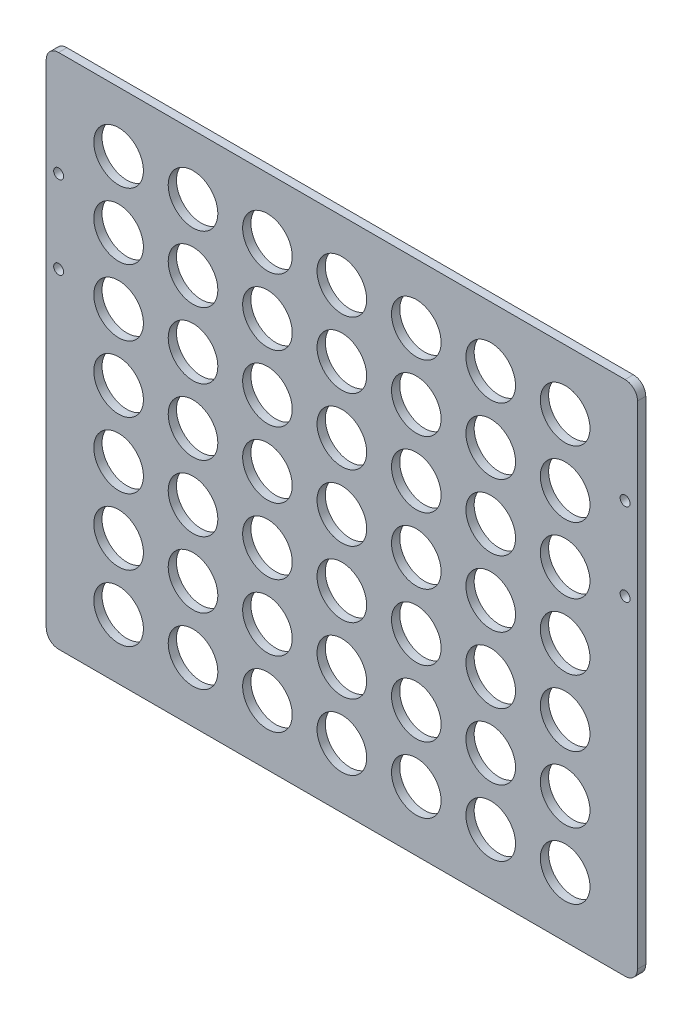
SolidWorks part; units mm, degrees
material "Thornel Mat VMA"
ref_plane "前视基准面" through (0, 0, 0) normal (0, 0, 1) x (1, 0, 0)
ref_plane "上视基准面" through (0, 0, 0) normal (0, 1, 0) x (1, 0, 0)
ref_plane "右视基准面" through (0, 0, 0) normal (1, 0, 0) x (0, 0, -1)
sketch "草图1" plane through (0, 0, 0) normal (0, 0, 1) x (1, 0, 0)
  line L1 (71.5, -62.5) -> (-71.5, -62.5)
  line L2 (71.5, -62.5) -> (71.5, 62.5)
  line L3 (71.5, 62.5) -> (-71.5, 62.5)
  line L4 (-71.5, -62.5) -> (-71.5, 62.5)
  line L5 (71.5, -62.5) -> (-71.5, 62.5) construction
  line L6 (71.5, 62.5) -> (-71.5, -62.5) construction
  point P0 (0, 0)
  dimension "D1" = 143
  dimension "D2" = 125
extrude "凸台-拉伸1" add sketch "草图1" along normal blind 2
fillet "圆角1" radius 3 4 edges at (71.5, 62.5, 1) (71.5, -62.5, 1) (-71.5, -62.5, 1) (-71.5, 62.5, 1)
sketch "草图2" plane through (0, 0, 0) normal (0, 0, -1) x (-1, 0, 0)
  line L0 (-71.5, 0) -> (71.5, 0) construction
  line L1 (-71.5, -59.5) -> (-71.5, 59.5) construction
  line L2 (71.5, 59.5) -> (71.5, -59.5) construction
  line L3 (0, 62.5) -> (0, -62.5) construction
  line L4 (-68.5, 62.5) -> (68.5, 62.5) construction
  line L5 (68.5, -62.5) -> (-68.5, -62.5) construction
  circle A0 centre (0, 0) radius 6
  circle A1 centre (18, 0) radius 6
  circle A2 centre (36, 0) radius 6
  circle A3 centre (54, 0) radius 6
  circle A4 centre (-54, 0) radius 6
  circle A5 centre (-36, 0) radius 6
  circle A6 centre (-18, 0) radius 6
  circle A7 centre (0, 16) radius 6
  circle A8 centre (18, 16) radius 6
  circle A9 centre (36, 16) radius 6
  circle A10 centre (54, 16) radius 6
  circle A11 centre (-54, 16) radius 6
  circle A12 centre (-36, 16) radius 6
  circle A13 centre (-18, 16) radius 6
  circle A14 centre (0, 32) radius 6
  circle A15 centre (18, 32) radius 6
  circle A16 centre (36, 32) radius 6
  circle A17 centre (54, 32) radius 6
  circle A18 centre (-54, 32) radius 6
  circle A19 centre (-36, 32) radius 6
  circle A20 centre (-18, 32) radius 6
  circle A21 centre (0, 48) radius 6
  circle A22 centre (18, 48) radius 6
  circle A23 centre (36, 48) radius 6
  circle A24 centre (54, 48) radius 6
  circle A25 centre (-54, 48) radius 6
  circle A26 centre (-36, 48) radius 6
  circle A27 centre (-18, 48) radius 6
  circle A28 centre (0, -16) radius 6
  circle A29 centre (18, -16) radius 6
  circle A30 centre (36, -16) radius 6
  circle A31 centre (54, -16) radius 6
  circle A32 centre (-54, -16) radius 6
  circle A33 centre (-36, -16) radius 6
  circle A34 centre (-18, -16) radius 6
  circle A35 centre (0, -32) radius 6
  circle A36 centre (18, -32) radius 6
  circle A37 centre (36, -32) radius 6
  circle A38 centre (54, -32) radius 6
  circle A39 centre (-54, -32) radius 6
  circle A40 centre (-36, -32) radius 6
  circle A41 centre (-18, -32) radius 6
  circle A42 centre (0, -48) radius 6
  circle A43 centre (18, -48) radius 6
  circle A44 centre (36, -48) radius 6
  circle A45 centre (54, -48) radius 6
  circle A46 centre (-54, -48) radius 6
  circle A47 centre (-36, -48) radius 6
  circle A48 centre (-18, -48) radius 6
  dimension "D1" = 12
  dimension "D2" = 4
extrude "切除-拉伸1" cut sketch "草图2" against normal blind 10
sketch "草图3" plane through (0, 0, 2) normal (0, 0, 1) x (1, 0, 0)
  line L1 (0, 62.5) -> (0, -62.5) construction
  line L2 (68.5, 62.5) -> (-68.5, 62.5) construction
  line L3 (-68.5, -62.5) -> (68.5, -62.5) construction
  line L4 (-71.5, 0) -> (71.5, 0) construction
  line L5 (-71.5, 59.5) -> (-71.5, -59.5) construction
  line L6 (71.5, -59.5) -> (71.5, 59.5) construction
  circle A0 centre (-68.5, 37.1255) radius 1.2 construction
  circle A1 centre (-68.5, 17.1255) radius 1.2 construction
  circle A2 centre (-68.5, 37.1255) radius 1.2
  circle A3 centre (-68.5, 17.1255) radius 1.2
  circle A4 centre (68.5, 17.1255) radius 1.2
  circle A5 centre (68.5, 37.1255) radius 1.2
extrude "切除-拉伸2" cut sketch "草图3" against normal blind 10
